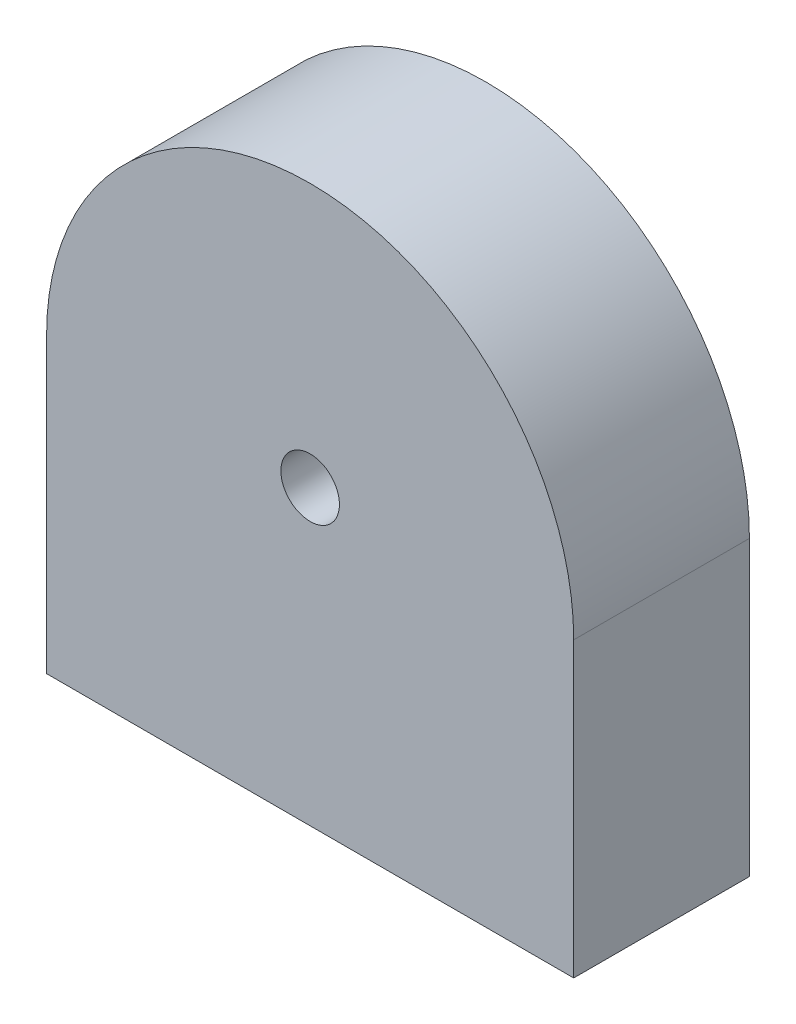
SolidWorks part; units mm, degrees
ref_plane "Front Plane" through (0, 0, 0) normal (0, 0, 1) x (1, 0, 0)
ref_plane "Top Plane" through (0, 0, 0) normal (0, 1, 0) x (1, 0, 0)
ref_plane "Right Plane" through (0, 0, 0) normal (1, 0, 0) x (0, 0, -1)
sketch "Sketch1" plane through (0, 0, 0) normal (0, 0, 1) x (1, 0, 0)
  line L1 (0, 0) -> (9, 0)
  line L2 (0, 0) -> (0, 5)
  line L4 (9, 0) -> (9, 5)
  arc A0 (9, 5) -> (0, 5) centre (4.5, 5) ccw
  circle A1 centre (4.5, 5) radius 0.5
  point P7 (4.5, 0)
  dimension "D3" = 1
  dimension "D4" = 4.5
  dimension "D1" = 9
  dimension "D2" = 5
extrude "Boss-Extrude1" add sketch "Sketch1" along normal blind 3
